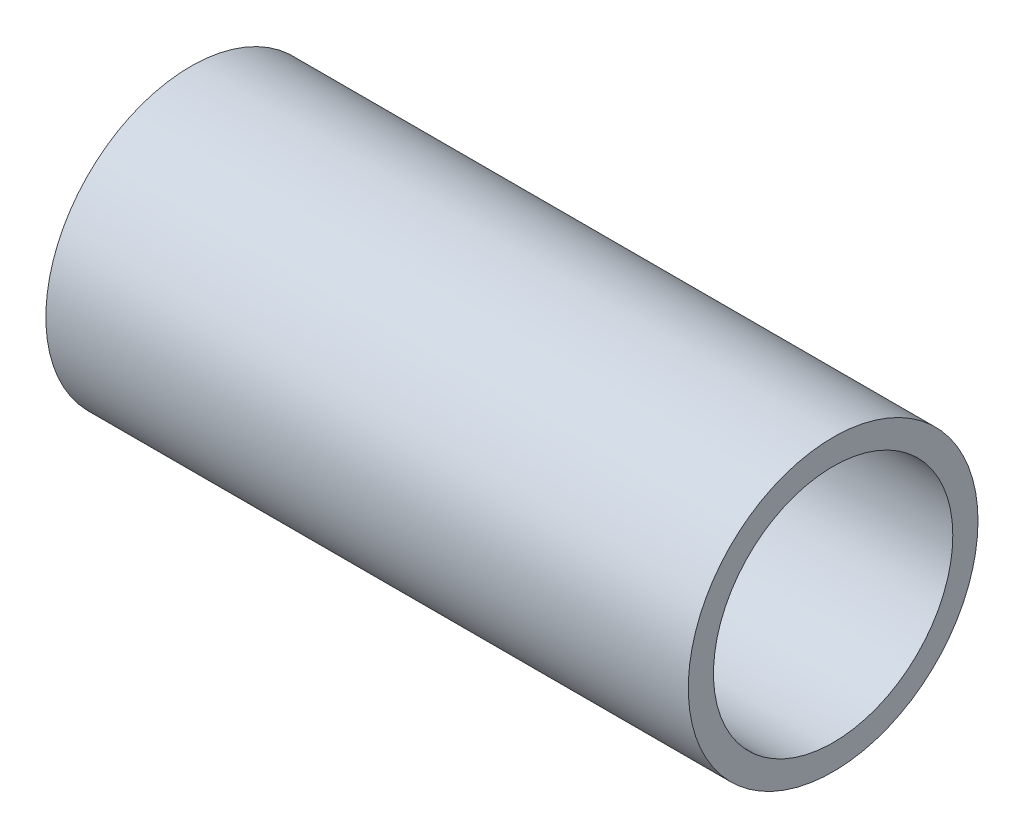
SolidWorks part; units mm, degrees
material "ABS"
ref_plane "Front" through (0, 0, 0) normal (0, 0, 1) x (1, 0, 0)
ref_plane "Top" through (0, 0, 0) normal (0, 1, 0) x (1, 0, 0)
ref_plane "Right" through (0, 0, 0) normal (1, 0, 0) x (0, 0, -1)
sketch "Esquisse1" plane through (0, 0, 0) normal (1, 0, 0) x (0, 0, -1)
  circle A0 centre (0, 0) radius 5.75
  dimension "D1" = 11.5
extrude "Extru.-Mince1" add sketch "Esquisse1" along normal blind 25.5 thin thin type one direction reverse wall 1
